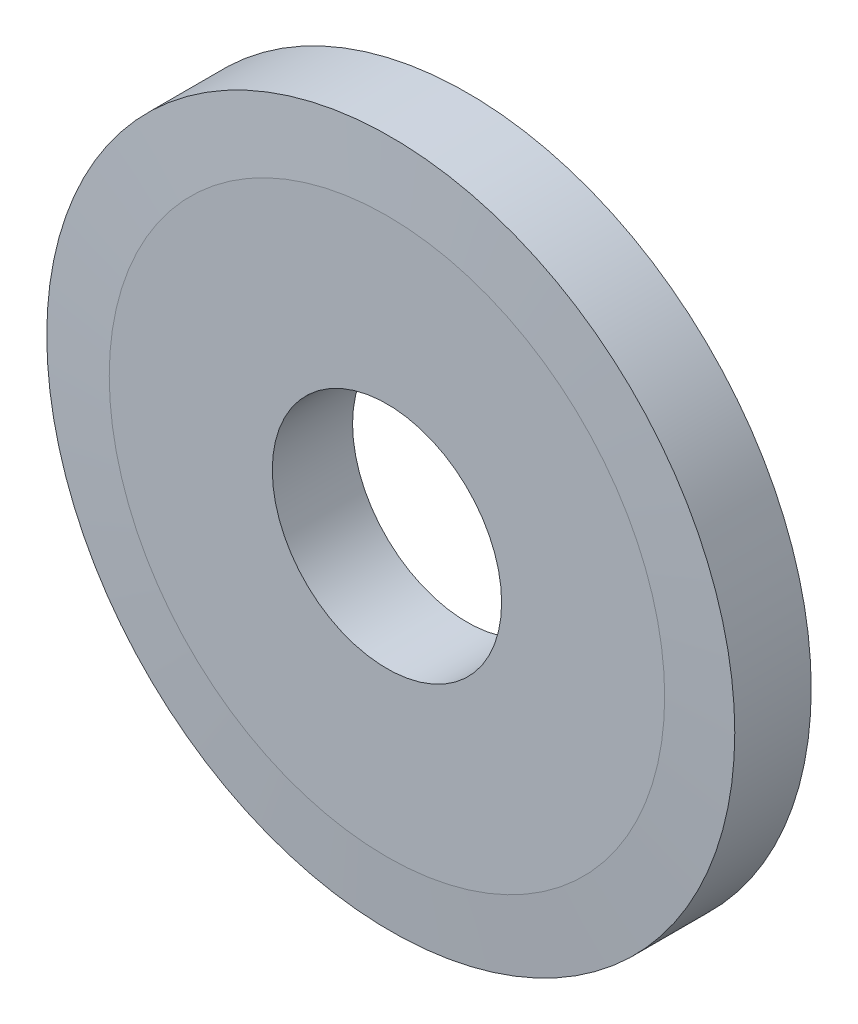
SolidWorks part; units mm, degrees
ref_plane "Front Plane" through (0, 0, 0) normal (0, 0, 1) x (1, 0, 0)
ref_plane "Top Plane" through (0, 0, 0) normal (0, 1, 0) x (1, 0, 0)
ref_plane "Right Plane" through (0, 0, 0) normal (1, 0, 0) x (0, 0, -1)
sketch "Sketch2" plane through (0, 0, 0) normal (0, 0, 1) x (1, 0, 0)
  circle A0 centre (0, 0) radius 9
  circle A1 centre (0, 0) radius 3
  dimension "D1" = 18
  dimension "D2" = 6
extrude "Boss-Extrude1" add sketch "Sketch2" along normal blind 2
ref_plane "Plane1" through (0, 0, 2.1) normal (0, 0, 1) x (1, 0, 0)
sketch "Sketch4" plane through (0, 0, 2) normal (0, 0, 1) x (1, 0, 0)
  circle A1 centre (0, 0) radius 9
  circle A2 centre (0, 0) radius 9
  dimension "D1" = 0
extrude "Boss-Extrude2" add sketch "Sketch4" along normal blind 0.1 draft 86.7
sketch "Sketch5" plane through (0, 0, 2) normal (0, 0, -1) x (-1, 0, 0)
  circle A1 centre (0, 0) radius 3
  circle A2 centre (0, 0) radius 3
  dimension "D1" = 0
extrude "Cut-Extrude1" cut sketch "Sketch5" against normal blind 0.1
